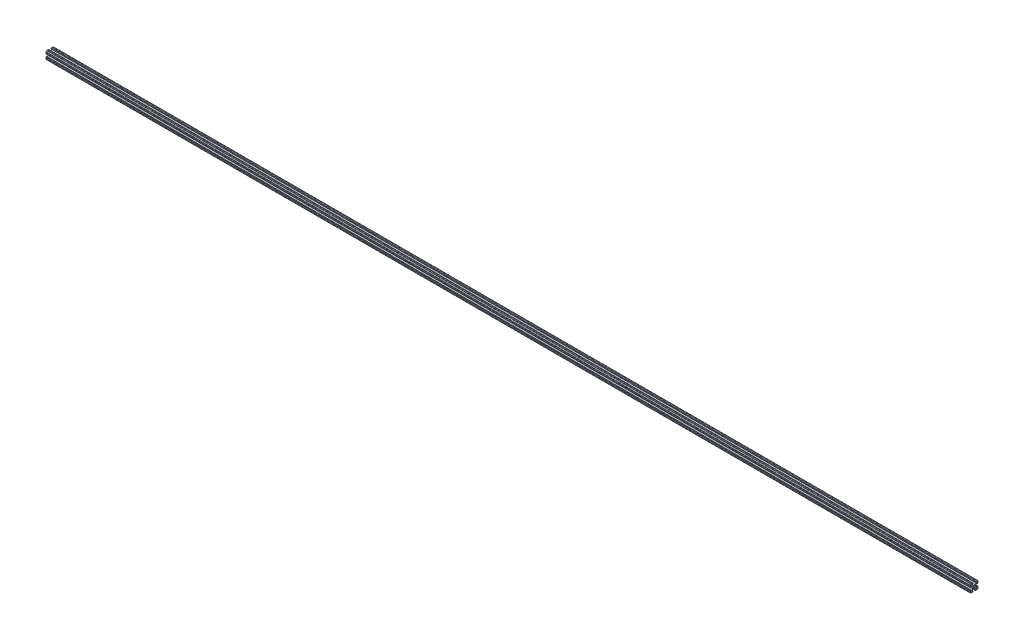
SolidWorks part; units mm, degrees
material "6061-T6 (SS)"
ref_plane "Front Plane" through (0, 0, 0) normal (0, 0, 1) x (1, 0, 0)
ref_plane "Top Plane" through (0, 0, 0) normal (0, 1, 0) x (1, 0, 0)
ref_plane "Right Plane" through (0, 0, 0) normal (1, 0, 0) x (0, 0, -1)
sketch "Sketch1" plane through (0, 0, 0) normal (1, 0, 0) x (0, 0, -1)
  line L0 (6.3331, -12.7) -> (9.5504, -12.7)
  line L1 (12.7, -9.5504) -> (12.7, -6.3331)
  line L2 (12.7, -5.3171) -> (12.7, -4.2875)
  line L3 (11.651, -3.2385) -> (11.5392, -3.2385)
  line L4 (10.4902, -4.2875) -> (10.4902, -6.4021)
  line L5 (8.7371, -7.1294) -> (5.441, -3.8408)
  line L6 (4.5085, -1.5932) -> (4.5085, 1.5932)
  line L7 (5.441, 3.8408) -> (8.7371, 7.1294)
  line L8 (10.4902, 6.4021) -> (10.4902, 4.2875)
  line L9 (11.5392, 3.2385) -> (11.651, 3.2385)
  line L10 (12.7, 4.2875) -> (12.7, 5.3171)
  line L11 (12.7, 6.3331) -> (12.7, 9.5504)
  line L12 (9.5504, 12.7) -> (6.3331, 12.7)
  line L13 (5.3171, 12.7) -> (4.2875, 12.7)
  line L14 (3.2385, 11.651) -> (3.2385, 11.5392)
  line L15 (4.2875, 10.4902) -> (6.4768, 10.4902)
  line L16 (7.207, 8.7244) -> (3.8983, 5.4232)
  line L17 (1.6558, 4.4958) -> (-1.6558, 4.4958)
  line L18 (-3.8983, 5.4232) -> (-7.207, 8.7244)
  line L19 (-6.4768, 10.4902) -> (-4.2875, 10.4902)
  line L20 (-3.2385, 11.5392) -> (-3.2385, 11.651)
  line L21 (-4.2875, 12.7) -> (-5.3171, 12.7)
  line L22 (-6.3331, 12.7) -> (-9.5504, 12.7)
  line L23 (-12.7, 9.5504) -> (-12.7, 6.3331)
  line L24 (-12.7, 5.3171) -> (-12.7, 4.2875)
  line L25 (-11.651, 3.2385) -> (-11.5392, 3.2385)
  line L26 (-10.4902, 4.2875) -> (-10.4902, 6.4021)
  line L27 (-8.7371, 7.1294) -> (-5.441, 3.8408)
  line L28 (-4.5085, 1.5932) -> (-4.5085, -1.5932)
  line L29 (-5.441, -3.8408) -> (-8.7371, -7.1294)
  line L30 (-10.4902, -6.4021) -> (-10.4902, -4.2875)
  line L31 (-11.5392, -3.2385) -> (-11.651, -3.2385)
  line L32 (-12.7, -4.2875) -> (-12.7, -5.3171)
  line L33 (-12.7, -6.3331) -> (-12.7, -9.5504)
  line L34 (-9.5504, -12.7) -> (-6.3331, -12.7)
  line L35 (-5.3171, -12.7) -> (-4.2875, -12.7)
  line L36 (-3.2385, -11.651) -> (-3.2385, -11.5392)
  line L37 (-4.2875, -10.4902) -> (-6.4164, -10.4902)
  line L38 (-7.1797, -8.6452) -> (-3.9523, -5.4237)
  line L39 (-1.7093, -4.4958) -> (1.7093, -4.4958)
  line L40 (3.9523, -5.4237) -> (7.1797, -8.6452)
  line L41 (6.4164, -10.4902) -> (4.2875, -10.4902)
  line L42 (3.2385, -11.5392) -> (3.2385, -11.651)
  line L43 (4.2875, -12.7) -> (5.3171, -12.7)
  circle A0 centre (0, 0) radius 2.6035
  arc A1 (6.3331, -12.7) -> (5.3171, -12.7) centre (5.8251, -12.7) ccw
  arc A2 (10.5664, -12.6998) -> (9.5504, -12.7) centre (10.0584, -12.7) ccw
  arc A3 (10.5664, -12.6998) -> (12.6998, -10.5664) centre (10.5918, -10.5918) ccw
  arc A4 (12.7, -9.5504) -> (12.6998, -10.5664) centre (12.7, -10.0584) ccw
  arc A5 (12.7, -5.3171) -> (12.7, -6.3331) centre (12.7, -5.8251) ccw
  arc A6 (12.7, -4.2875) -> (11.651, -3.2385) centre (11.651, -4.2875) ccw
  arc A7 (11.5392, -3.2385) -> (10.4902, -4.2875) centre (11.5392, -4.2875) ccw
  arc A8 (8.7371, -7.1294) -> (10.4902, -6.4021) centre (9.4628, -6.4021) ccw
  arc A9 (5.441, 3.8408) -> (4.5085, 1.5932) centre (7.6835, 1.5932) ccw
  arc A10 (10.4902, 6.4021) -> (8.7371, 7.1294) centre (9.4628, 6.4021) ccw
  arc A11 (10.4902, 4.2875) -> (11.5392, 3.2385) centre (11.5392, 4.2875) ccw
  arc A12 (11.651, 3.2385) -> (12.7, 4.2875) centre (11.651, 4.2875) ccw
  arc A13 (12.7, 6.3331) -> (12.7, 5.3171) centre (12.7, 5.8251) ccw
  arc A14 (12.6998, 10.5664) -> (12.7, 9.5504) centre (12.7, 10.0584) ccw
  arc A15 (12.6998, 10.5664) -> (10.5664, 12.6998) centre (10.5918, 10.5918) ccw
  arc A16 (9.5504, 12.7) -> (10.5664, 12.6998) centre (10.0584, 12.7) ccw
  arc A17 (5.3171, 12.7) -> (6.3331, 12.7) centre (5.8251, 12.7) ccw
  arc A18 (4.2875, 12.7) -> (3.2385, 11.651) centre (4.2875, 11.651) ccw
  arc A19 (3.2385, 11.5392) -> (4.2875, 10.4902) centre (4.2875, 11.5392) ccw
  arc A20 (7.207, 8.7244) -> (6.4768, 10.4902) centre (6.4768, 9.4563) ccw
  arc A21 (1.6558, 4.4958) -> (3.8983, 5.4232) centre (1.6558, 7.6708) ccw
  arc A22 (-3.8983, 5.4232) -> (-1.6558, 4.4958) centre (-1.6558, 7.6708) ccw
  arc A23 (-6.4768, 10.4902) -> (-7.207, 8.7244) centre (-6.4768, 9.4563) ccw
  arc A24 (-4.2875, 10.4902) -> (-3.2385, 11.5392) centre (-4.2875, 11.5392) ccw
  arc A25 (-3.2385, 11.651) -> (-4.2875, 12.7) centre (-4.2875, 11.651) ccw
  arc A26 (-6.3331, 12.7) -> (-5.3171, 12.7) centre (-5.8251, 12.7) ccw
  arc A27 (-10.5664, 12.6998) -> (-9.5504, 12.7) centre (-10.0584, 12.7) ccw
  arc A28 (-10.5664, 12.6998) -> (-12.6998, 10.5664) centre (-10.5918, 10.5918) ccw
  arc A29 (-12.7, 9.5504) -> (-12.6998, 10.5664) centre (-12.7, 10.0584) ccw
  arc A30 (-12.7, 5.3171) -> (-12.7, 6.3331) centre (-12.7, 5.8251) ccw
  arc A31 (-12.7, 4.2875) -> (-11.651, 3.2385) centre (-11.651, 4.2875) ccw
  arc A32 (-11.5392, 3.2385) -> (-10.4902, 4.2875) centre (-11.5392, 4.2875) ccw
  arc A33 (-8.7371, 7.1294) -> (-10.4902, 6.4021) centre (-9.4628, 6.4021) ccw
  arc A34 (-4.5085, 1.5932) -> (-5.441, 3.8408) centre (-7.6835, 1.5932) ccw
  arc A35 (-5.441, -3.8408) -> (-4.5085, -1.5932) centre (-7.6835, -1.5932) ccw
  arc A36 (-10.4902, -6.4021) -> (-8.7371, -7.1294) centre (-9.4628, -6.4021) ccw
  arc A37 (-10.4902, -4.2875) -> (-11.5392, -3.2385) centre (-11.5392, -4.2875) ccw
  arc A38 (-11.651, -3.2385) -> (-12.7, -4.2875) centre (-11.651, -4.2875) ccw
  arc A39 (-12.7, -6.3331) -> (-12.7, -5.3171) centre (-12.7, -5.8251) ccw
  arc A40 (-12.6998, -10.5664) -> (-12.7, -9.5504) centre (-12.7, -10.0584) ccw
  arc A41 (-12.6998, -10.5664) -> (-10.5664, -12.6998) centre (-10.5918, -10.5918) ccw
  arc A42 (-9.5504, -12.7) -> (-10.5664, -12.6998) centre (-10.0584, -12.7) ccw
  arc A43 (-5.3171, -12.7) -> (-6.3331, -12.7) centre (-5.8251, -12.7) ccw
  arc A44 (-4.2875, -12.7) -> (-3.2385, -11.651) centre (-4.2875, -11.651) ccw
  arc A45 (-3.2385, -11.5392) -> (-4.2875, -10.4902) centre (-4.2875, -11.5392) ccw
  arc A46 (-7.1797, -8.6452) -> (-6.4164, -10.4902) centre (-6.4164, -9.4098) ccw
  arc A47 (-1.7093, -4.4958) -> (-3.9523, -5.4237) centre (-1.7093, -7.6708) ccw
  arc A48 (3.9523, -5.4237) -> (1.7093, -4.4958) centre (1.7093, -7.6708) ccw
  arc A49 (6.4164, -10.4902) -> (7.1797, -8.6452) centre (6.4164, -9.4098) ccw
  arc A50 (4.2875, -10.4902) -> (3.2385, -11.5392) centre (4.2875, -11.5392) ccw
  arc A51 (3.2385, -11.651) -> (4.2875, -12.7) centre (4.2875, -11.651) ccw
  arc A52 (5.441, -3.8408) -> (4.5085, -1.5932) centre (7.6835, -1.5932) cw
  dimension "D1" = 3.175
extrude "Boss-Extrude1" add sketch "Sketch1" along normal mid plane 3048
